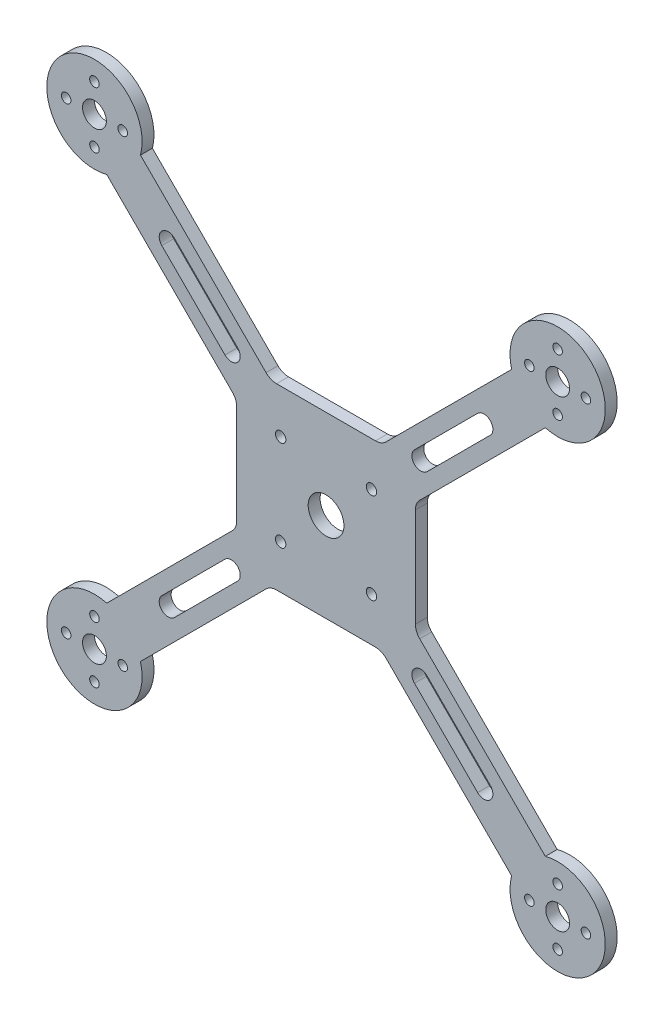
SolidWorks part; units mm, degrees
ref_plane "前视基准面" through (0, 0, 0) normal (0, 0, 1) x (1, 0, 0)
ref_plane "上视基准面" through (0, 0, 0) normal (0, 1, 0) x (1, 0, 0)
ref_plane "右视基准面" through (0, 0, 0) normal (1, 0, 0) x (0, 0, -1)
sketch "草图1" plane through (0, 0, 0) normal (0, 0, 1) x (1, 0, 0)
  line L0 (-30, -30) -> (30, -30)
  line L1 (30, -30) -> (30, 30)
  line L2 (30, 30) -> (-30, 30)
  line L3 (-30, 30) -> (-30, -30)
extrude "凸台-拉伸1" add sketch "草图1" along normal blind 4
sketch "草图2" plane through (0, 0, 0) normal (0, 0, 1) x (1, 0, 0)
  line L0 (18.6863, 30) -> (72.1248, 83.4385)
  line L1 (72.1248, 83.4385) -> (83.4385, 72.1248)
  line L2 (83.4385, 72.1248) -> (30, 18.6863)
  line L3 (30, 18.6863) -> (18.6863, 30)
  line L4 (-18.6863, 30) -> (-72.1248, 83.4385)
  line L5 (-72.1248, 83.4385) -> (-83.4385, 72.1248)
  line L6 (-83.4385, 72.1248) -> (-30, 18.6863)
  line L7 (-30, 18.6863) -> (-18.6863, 30)
  line L8 (-30, -18.6863) -> (-83.4385, -72.1248)
  line L9 (-83.4385, -72.1248) -> (-72.1248, -83.4385)
  line L10 (-72.1248, -83.4385) -> (-18.6863, -30)
  line L11 (-18.6863, -30) -> (-30, -18.6863)
  line L12 (30, -18.6863) -> (83.4385, -72.1248)
  line L13 (83.4385, -72.1248) -> (72.1248, -83.4385)
  line L14 (72.1248, -83.4385) -> (18.6863, -30)
  line L15 (18.6863, -30) -> (30, -18.6863)
extrude "凸台-拉伸2" add sketch "草图2" along normal blind 4
sketch "草图3" plane through (0, 0, 0) normal (0, 0, 1) x (1, 0, 0)
  circle A0 centre (77.7817, 77.7817) radius 16
  circle A1 centre (-77.7817, 77.7817) radius 16
  circle A2 centre (-77.7817, -77.7817) radius 16
  circle A3 centre (77.7817, -77.7817) radius 16
extrude "凸台-拉伸3" add sketch "草图3" along normal blind 4
sketch "草图4" plane through (0, 0, 0) normal (0, 0, 1) x (1, 0, 0)
  circle A0 centre (0, 0) radius 6
extrude "切除-拉伸1" cut sketch "草图4" along normal through all
sketch "草图5" plane through (0, 0, 0) normal (0, 0, 1) x (1, 0, 0)
  circle A0 centre (15.25, 15.25) radius 1.75
  circle A1 centre (-15.25, 15.25) radius 1.75
  circle A2 centre (-15.25, -15.25) radius 1.75
  circle A3 centre (15.25, -15.25) radius 1.75
extrude "切除-拉伸2" cut sketch "草图5" along normal through all
sketch "草图6" plane through (0, 0, 0) normal (0, 0, 1) x (1, 0, 0)
  circle A0 centre (77.7817, 77.7817) radius 4
  circle A1 centre (-77.7817, 77.7817) radius 4
  circle A2 centre (-77.7817, -77.7817) radius 4
  circle A3 centre (77.7817, -77.7817) radius 4
extrude "切除-拉伸3" cut sketch "草图6" along normal through all
sketch "草图7" plane through (0, 0, 0) normal (0, 0, 1) x (1, 0, 0)
  circle A0 centre (87.2817, 77.7817) radius 1.6
  circle A1 centre (68.2817, 77.7817) radius 1.6
  circle A2 centre (77.7817, 87.2817) radius 1.6
  circle A3 centre (77.7817, 68.2817) radius 1.6
  circle A4 centre (-87.2817, 77.7817) radius 1.6
  circle A5 centre (-68.2817, 77.7817) radius 1.6
  circle A6 centre (-77.7817, 87.2817) radius 1.6
  circle A7 centre (-77.7817, 68.2817) radius 1.6
  circle A8 centre (-87.2817, -77.7817) radius 1.6
  circle A9 centre (-68.2817, -77.7817) radius 1.6
  circle A10 centre (-77.7817, -87.2817) radius 1.6
  circle A11 centre (-77.7817, -68.2817) radius 1.6
  circle A12 centre (87.2817, -77.7817) radius 1.6
  circle A13 centre (68.2817, -77.7817) radius 1.6
  circle A14 centre (77.7817, -87.2817) radius 1.6
  circle A15 centre (77.7817, -68.2817) radius 1.6
extrude "切除-拉伸4" cut sketch "草图7" along normal through all
sketch "草图8" plane through (0, 0, 0) normal (0, 0, 1) x (1, 0, 0)
  line L0 (33.9411, 29.6985) -> (55.1543, 50.9117)
  line L1 (50.9117, 55.1543) -> (29.6985, 33.9411)
  line L2 (-29.6985, 33.9411) -> (-50.9117, 55.1543)
  line L3 (-55.1543, 50.9117) -> (-33.9411, 29.6985)
  line L4 (-33.9411, -29.6985) -> (-55.1543, -50.9117)
  line L5 (-50.9117, -55.1543) -> (-29.6985, -33.9411)
  line L6 (29.6985, -33.9411) -> (50.9117, -55.1543)
  line L7 (55.1543, -50.9117) -> (33.9411, -29.6985)
  arc A0 (55.1543, 50.9117) -> (50.9117, 55.1543) centre (53.033, 53.033) ccw
  arc A1 (29.6985, 33.9411) -> (33.9411, 29.6985) centre (31.8198, 31.8198) ccw
  arc A2 (-50.9117, 55.1543) -> (-55.1543, 50.9117) centre (-53.033, 53.033) ccw
  arc A3 (-33.9411, 29.6985) -> (-29.6985, 33.9411) centre (-31.8198, 31.8198) ccw
  arc A4 (-55.1543, -50.9117) -> (-50.9117, -55.1543) centre (-53.033, -53.033) ccw
  arc A5 (-29.6985, -33.9411) -> (-33.9411, -29.6985) centre (-31.8198, -31.8198) ccw
  arc A6 (50.9117, -55.1543) -> (55.1543, -50.9117) centre (53.033, -53.033) ccw
  arc A7 (33.9411, -29.6985) -> (29.6985, -33.9411) centre (31.8198, -31.8198) ccw
extrude "切除-拉伸5" cut sketch "草图8" along normal through all
fillet "圆角1" radius 5 8 edges at (30, -18.6863, 2) (18.6863, -30, 2) (-18.6863, -30, 2) (-30, -18.6863, 2) (-30, 18.6863, 2) (-18.6863, 30, 2) (18.6863, 30, 2) (30, 18.6863, 2)
